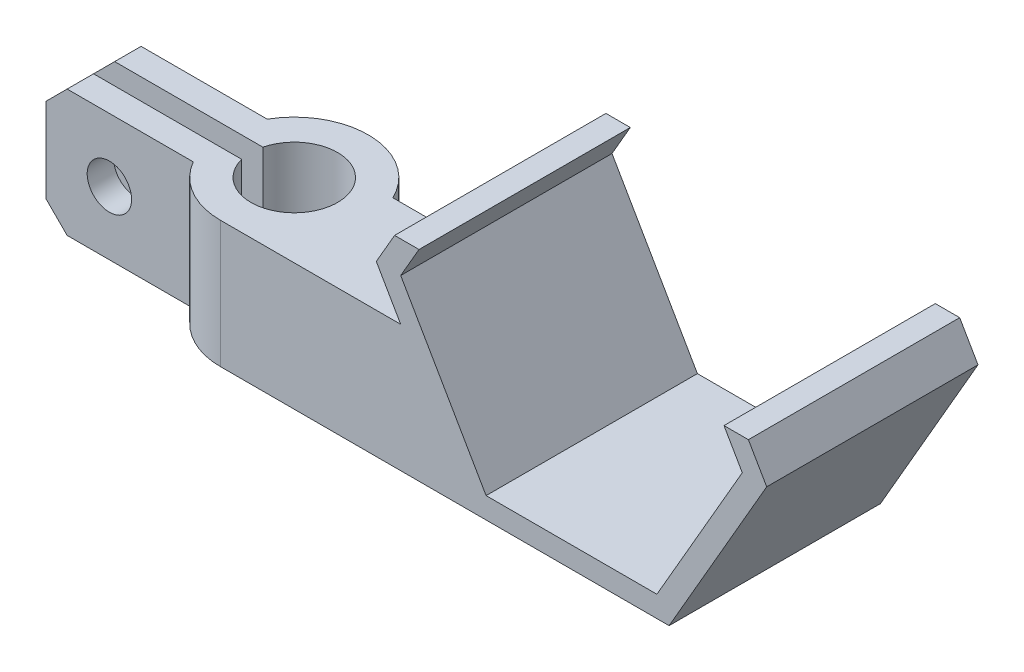
SolidWorks part; units mm, degrees
ref_plane "Přední rovina" through (0, 0, 0) normal (0, 0, 1) x (1, 0, 0)
ref_plane "Horní rovina" through (0, 0, 0) normal (0, 1, 0) x (1, 0, 0)
ref_plane "Pravá rovina" through (0, 0, 0) normal (1, 0, 0) x (0, 0, -1)
sketch "Skica1" plane through (0, 0, 0) normal (0, 0, 1) x (1, 0, 0)
  line L0 (-14.4338, 3) -> (-16.1658, 0)
  line L1 (13.8564, 0) -> (6.9282, 12) construction
  line L2 (6.9282, 12) -> (-6.9282, 12) construction
  line L3 (-6.9282, 12) -> (-13.8564, 0) construction
  line L4 (-13.8564, 0) -> (-6.9282, -12) construction
  line L5 (-6.9282, -12) -> (6.9282, -12) construction
  line L6 (6.9282, -12) -> (13.8564, 0) construction
  line L7 (-16.1658, 0) -> (-8.0829, -14)
  line L8 (-8.0829, -14) -> (8.0829, -14)
  line L9 (8.0829, -14) -> (16.1658, 0)
  line L10 (16.1658, 0) -> (14.4338, 3)
  line L11 (-14.4338, 3) -> (14.4338, 3) construction
  line L12 (-16.7432, 3) -> (-18.4752, 0)
  line L13 (-18.4752, 0) -> (-9.2376, -16)
  line L14 (-9.2376, -16) -> (9.2376, -16)
  line L15 (9.2376, -16) -> (18.4752, 0)
  line L16 (18.4752, 0) -> (16.7432, 3)
  line L17 (-14.4338, 3) -> (-16.7432, 3)
  line L18 (14.4338, 3) -> (16.7432, 3)
  line L19 (-10.3923, 14) -> (-18.4752, 0) construction
  line L20 (-8.6603, 13) -> (-16.1658, 0) construction
  line L21 (18.4752, 0) -> (10.3923, 14) construction
  line L22 (16.1658, 0) -> (8.6603, 13) construction
  circle A0 centre (0, 0) radius 12 construction
  dimension "D1" = 24
  dimension "D2" = 6.9282
  dimension "D4" = 3
  dimension "D3" = 2
  dimension "D5" = 2
extrude "Přidat vysunutím1" add sketch "Skica1" along normal blind 20
ref_plane "Rovina1" through (0, 0, 10) normal (0, 0, 1) x (1, 0, 0)
sketch "Skica2" plane through (0, 0, 10) normal (0, 0, 1) x (1, 0, 0)
  line L0 (-9.2376, -16) -> (-29.2376, -16)
  line L1 (-29.2376, -16) -> (-29.2376, -4)
  line L3 (-16.1658, -4) -> (-9.2376, -16)
  line L4 (-29.2376, -4) -> (-16.1658, -4)
  dimension "D1" = 20
  dimension "D2" = 12
  dimension "D3" = 6.9282
extrude "Přidat vysunutím2" add sketch "Skica2" along normal blind 10
sketch "Skica3" plane through (0, 0, 0) normal (0, 1, 0) x (1, 0, 0)
  line L6 (-29.2376, -10) -> (-26.913, -10)
  line L12 (-18.4752, -20) -> (-18.4752, 0) construction
  line L14 (-29.2376, -10) -> (-29.2376, -12.1)
  line L15 (-53.2376, -16.5) -> (-53.2376, -14)
  line L16 (-53.2376, -14) -> (-37.2138, -14)
  line L17 (-53.2376, -12) -> (-37.2138, -12)
  line L18 (-53.2376, -12) -> (-53.2376, -9.5)
  line L19 (-53.2376, -9.5) -> (-39.2998, -9.5)
  line L24 (-33.2376, -20) -> (-29.2376, -20)
  line L25 (-29.2376, -13.9) -> (-29.2376, -20)
  line L26 (-16.1658, -10) -> (-29.2376, -10) construction
  line L27 (-29.2376, -20) -> (-29.2376, -10) construction
  line L28 (-53.2376, -16.5) -> (-39.2998, -16.5)
  arc A7 (-39.2998, -16.5) -> (-33.2376, -20) centre (-33.2376, -13) ccw
  arc A8 (-26.913, -10) -> (-39.2998, -9.5) centre (-33.2376, -13) ccw
  arc A10 (-29.2376, -12.1) -> (-37.2138, -12) centre (-33.2376, -13) ccw
  arc A11 (-37.2138, -14) -> (-29.2376, -13.9) centre (-33.2376, -13) ccw
  dimension "D3" = 2
  dimension "D5" = 8.2
  dimension "D12" = 24
  dimension "D15" = 7
  dimension "D4" = 4
  dimension "D6" = 2.5
  dimension "D7" = 2
  dimension "D2" = 8.4378
  dimension "D8" = 2.5
  dimension "D13" = 24
  dimension "D14" = 10
extrude "Přidat vysunutím3" add sketch "Skica3" along normal up to surface (12 mm away) from surface
sketch "Skica4" plane through (0, 0, 0) normal (0, 1, 0) x (1, 0, 0)
  circle A2 centre (-33.2376, -13) radius 4.1
extrude "Odebrat vysunutím1" cut sketch "Skica4" against normal through all from surface at -4 starting at face at (-36.941, -4, 13.362)
sketch "Skica11" plane through (0, 0, 16.5) normal (0, 0, 1) x (1, 0, 0)
  line L0 (-53.2376, -16) -> (-53.2376, -4) construction
  line L2 (-39.2998, -4) -> (-53.2376, -4) construction
  circle A0 centre (-47.2376, -10) radius 2.1
  dimension "D2" = 4.2
  dimension "D1" = 6
  dimension "D3" = 6
extrude "Odebrat vysunutím5" cut sketch "Skica11" against normal up to next
sketch "Skica12" plane through (0, 0, 9.5) normal (0, 0, -1) x (-1, 0, 0)
  line L0 (53.2376, -10) -> (47.2376, -10)
  line L1 (53.2376, -16) -> (53.2376, -4) construction
  circle A0 centre (47.2376, -10) radius 2.8
  dimension "D2" = 5.6
  dimension "D1" = 6
extrude "Odebrat vysunutím6" cut sketch "Skica12" against normal up to next
chamfer "Zkosení2" distance 2 angle 45 4 edges at (-53.2376, -16, 15.25) (-53.2376, -4, 15.25) (-53.2376, -16, 10.75) (-53.2376, -4, 10.75)
sketch "Skica13" plane through (0, 0, 9.5) normal (0, 0, -1) x (-1, 0, 0)
  circle A0 centre (47.2376, -10) radius 2.8
  circle A1 centre (47.2376, -10) radius 4.5
  dimension "D1" = 5.6
  dimension "D2" = 9
extrude "Přidat vysunutím5" add sketch "Skica13" along normal blind 1
